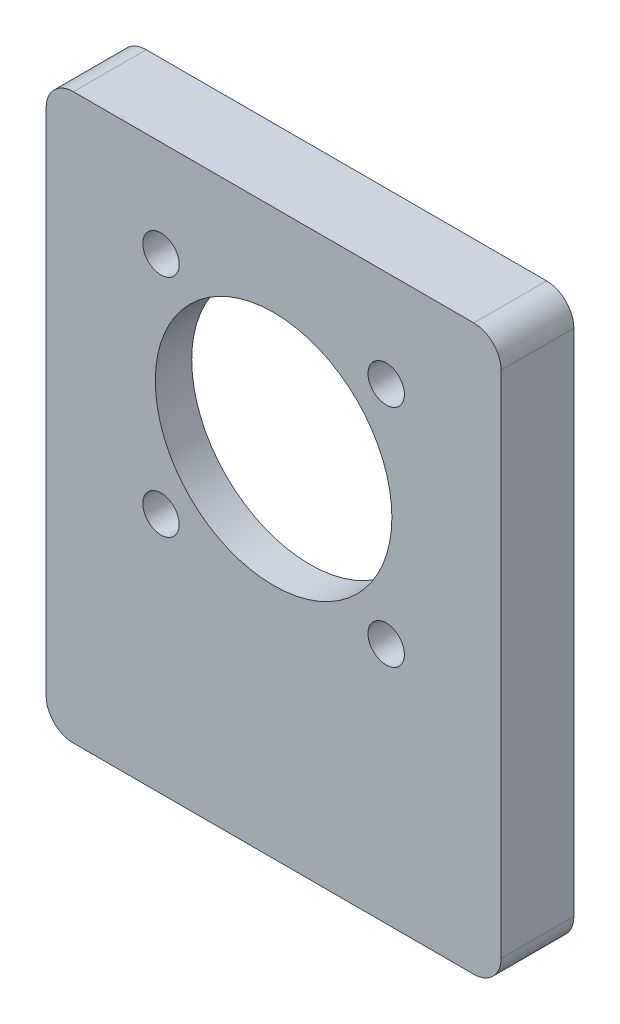
SolidWorks part; units mm, degrees
material "6061 合金"
ref_plane "前视基准面" through (0, 0, 0) normal (0, 0, 1) x (1, 0, 0)
ref_plane "上视基准面" through (0, 0, 0) normal (0, 1, 0) x (1, 0, 0)
ref_plane "右视基准面" through (0, 0, 0) normal (1, 0, 0) x (0, 0, -1)
sketch "草图1" plane through (0, 0, 0) normal (0, 0, 1) x (1, 0, 0)
  line L1 (-25, 31) -> (25, 31)
  line L2 (-25, 31) -> (-25, -31)
  line L3 (-25, -31) -> (25, -31)
  line L4 (25, 31) -> (25, -31)
  line L5 (-25, 31) -> (25, -31) construction
  line L6 (-25, -31) -> (25, 31) construction
  point P0 (0, 0)
  dimension "D1" = 62
  dimension "D2" = 50
extrude "凸台-拉伸1" add sketch "草图1" along normal blind 8
sketch "草图2" plane through (0, 0, 8) normal (0, 0, 1) x (1, 0, 0)
  line L0 (0, 18.5643) -> (0, -18.2311) construction
  line L2 (12.3744, 20.3744) -> (0, 8) construction
  line L3 (0, 8) -> (28.1071, 8) construction
  line L4 (25, 31) -> (-25, 31) construction
  circle A0 centre (0, 8) radius 13
  circle A1 centre (0, 8) radius 17.5 construction
  circle A2 centre (12.3744, 20.3744) radius 2
  circle A3 centre (12.3744, -4.3744) radius 2
  circle A4 centre (-12.3744, -4.3744) radius 2
  circle A5 centre (-12.3744, 20.3744) radius 2
  point P11 (-25.0449, 34.9578)
  point P12 (0, 22)
  point P20 (0, 8)
  dimension "D1" = 26
  dimension "D2" = 35
  dimension "D3" = 4
  dimension "D4" = 23
  dimension "D5" = 45
  dimension "D6" = 4
extrude "切除-拉伸1" cut sketch "草图2" against normal through all
sketch "草图3" plane through (0, -31, 0) normal (0, -1, 0) x (1, 0, 0)
  line L0 (25, 4) -> (-25, 4) construction
  line L1 (25, 8) -> (25, 0) construction
  line L2 (-25, 8) -> (-25, 0) construction
  line L3 (0, 13.9154) -> (0, -8.0273) construction
  point P6 (-15, 4)
  point P7 (15, 4)
  dimension "D1" = 30
hole_wizard "M5 螺纹孔1" positions "3D草图1" profile "草图5" tap size "M5" standard "GB"
sketch3d "3D草图1"
  point P0 (-15, -31, 4)
  point P3 (15, -31, 4)
sketch "草图5" plane through (-15, -31, 4) normal (1, 0, 0) x (0, 0, -1)
  line L0 (0, 0) -> (0, 16.2618)
  line L1 (0, 16.2618) -> (2.1, 15)
  line L2 (2.1, 15) -> (2.1, 0.425)
  line L3 (2.1, 0.425) -> (2.525, 0)
  line L5 (2.525, 0) -> (0, 0)
  line L6 (-2.1, 0.425) -> (-2.525, 0) construction
  line L10 (0, 16.2618) -> (-2.1, 15) construction
  line L11 (0, -6.35) -> (0, 107.95) construction
  dimension "螺纹孔钻头直径" = 4.2
  dimension "螺纹孔钻头深度" = 15
  dimension "近端锥形沉头孔直径" = 5.05
  dimension "近端锥形沉头孔角度" = 90
  dimension "导头角度" = 118
cosmetic thread "孔螺蚊线1" parameters "D1"=10, "D2"=5
cosmetic thread "孔螺蚊线2" parameters "D1"=10, "D2"=5
fillet "圆角1" radius 3 4 edges at (25, -31, 4) (-25, 31, 4) (25, 31, 4) (-25, -31, 4)
sketch "草图6" plane through (0, 0, 0) normal (0, 0, -1) x (-1, 0, 0)
  circle A0 centre (0, 8) radius 21.25
  dimension "D1" = 42.5
extrude "切除-拉伸2" cut sketch "草图6" against normal blind 4
chamfer "倒角1" distance 0.5 angle 45 1 edges at (-21.25, 8, 0)
